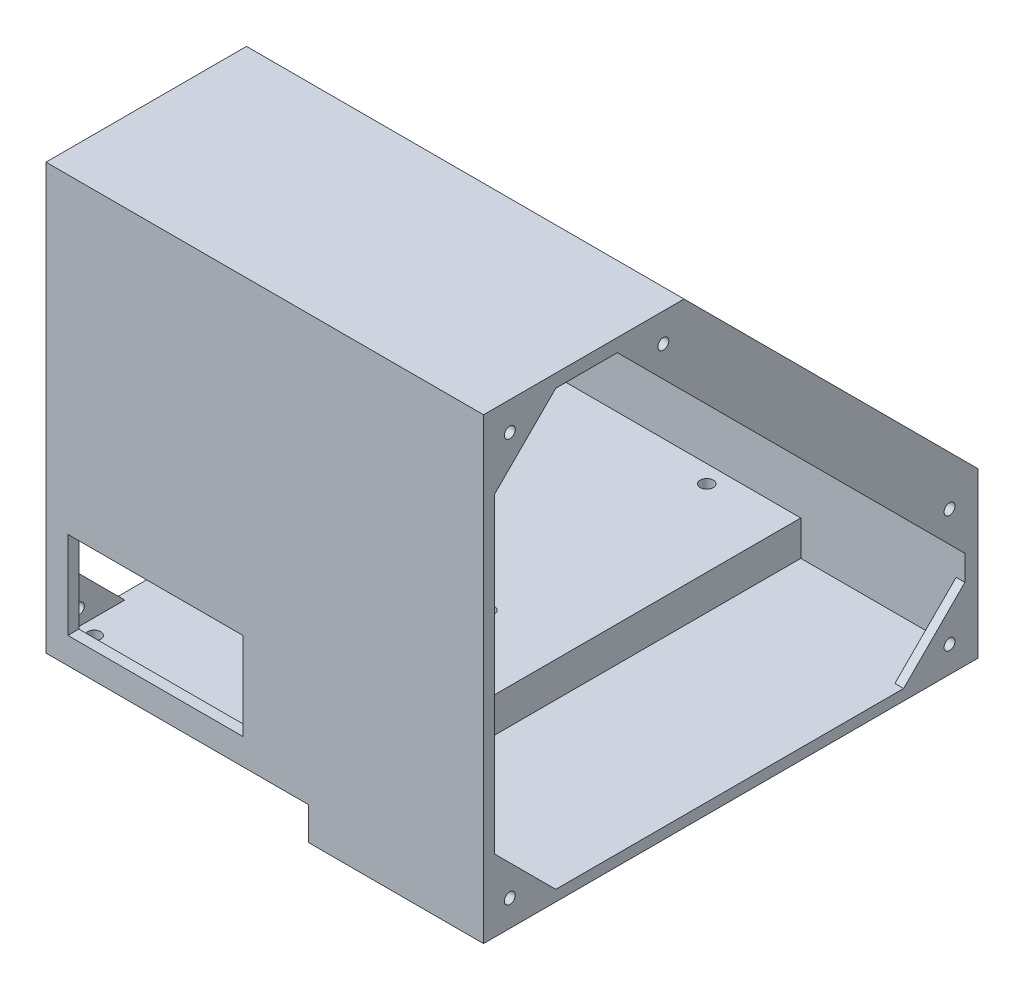
SolidWorks part; units mm, degrees
ref_plane "Front Plane" through (0, 0, 0) normal (0, 0, 1) x (1, 0, 0)
ref_plane "Top Plane" through (0, 0, 0) normal (0, 1, 0) x (1, 0, 0)
ref_plane "Right Plane" through (0, 0, 0) normal (1, 0, 0) x (0, 0, -1)
sketch "Sketch1" plane through (0, 0, 0) normal (1, 0, 0) x (0, 0, -1)
  line L0 (0, 0) -> (0, 30)
  line L1 (0, 30) -> (-67.1751, 97.1751)
  line L2 (-67.1751, 97.1751) -> (-113, 97.1751)
  line L3 (-113, 97.1751) -> (-113, 94.1751)
  line L4 (-113, 94.1751) -> (-68.4178, 94.1751)
  line L5 (-68.4178, 94.1751) -> (-3, 28.7574)
  line L6 (-3, 28.7574) -> (-3, 0)
  line L7 (-3, 0) -> (0, 0)
  line L8 (-3, 28.7574) -> (0, 28.7574) construction
  line L9 (-3, 28.7574) -> (-0.8787, 30.8787) construction
  line L10 (-68.4178, 94.1751) -> (-68.4178, 97.1751) construction
  point P3 (-68.4178, 90.8281)
  point P14 (-66.2965, 92.1818)
  dimension "D1" = 95
  dimension "D2" = 135
  dimension "D3" = 3
  dimension "D4" = 30
  dimension "D5" = 110
extrude "Boss-Extrude1" add sketch "Sketch1" along normal blind 100
sketch "Sketch2" plane through (0, 0, 0) normal (0, -1, 0) x (1, 0, 0)
  line L0 (100, 0) -> (0, 0) construction
  line L1 (100, 3) -> (60, 3)
  line L2 (100, 3) -> (100, 0)
  line L3 (100, 0) -> (60, 0)
  line L4 (60, 3) -> (60, 0)
  dimension "D1" = 40
extrude "Boss-Extrude2" add sketch "Sketch2" along normal blind 7.5
sketch "Sketch3" plane through (0, 0, 0) normal (0, -1, 0) x (1, 0, 0)
  line L0 (0, 3) -> (0, 113)
  line L1 (0, 113) -> (60, 113)
  line L2 (60, 113) -> (60, 3)
  line L3 (60, 3) -> (0, 3)
  line L4 (100, 3) -> (0, 3) construction
  line L5 (60, 3) -> (0, 3) construction
  point P4 (60, 3)
  dimension "D1" = 110
extrude "Boss-Extrude3" add sketch "Sketch3" against normal blind 3
sketch "Sketch4" plane through (0, 0, 3) normal (0, 0, 1) x (1, 0, 0)
  line L0 (60, 3) -> (60, -7.5)
  line L1 (60, -7.5) -> (100, -7.5)
  line L2 (100, -7.5) -> (100, -5)
  line L3 (100, 28.7574) -> (100, -7.5) construction
  line L4 (100, -5) -> (62.5, -5)
  line L5 (62.5, -5) -> (62.5, 3)
  line L6 (62.5, 3) -> (60, 3)
  dimension "D1" = 2.5
extrude "Boss-Extrude4" add sketch "Sketch4" along normal up to surface (110 mm away) up to face at (30, 1.5, 113)
sketch "Sketch5" plane through (0, 94.1751, 0) normal (0, -1, 0) x (1, 0, 0)
  line L0 (100, 113) -> (100, 68.4178) construction
  line L1 (0, 113) -> (100, 113)
  line L2 (0, 113) -> (0, 110.5)
  line L3 (0, 110.5) -> (100, 110.5)
  line L4 (100, 113) -> (100, 110.5)
  dimension "D1" = 2.5
extrude "Boss-Extrude5" add sketch "Sketch5" along normal up to next
sketch "Sketch6" plane through (0, 0, 0) normal (0, -1, 0) x (1, 0, 0)
  circle A0 centre (5, 107) radius 1.5 construction
  circle A1 centre (45, 107) radius 1.5 construction
  circle A2 centre (45, 57) radius 1.5 construction
  circle A3 centre (5, 57) radius 1.5 construction
  circle A4 centre (5, 7) radius 1.5 construction
  circle A5 centre (45, 7) radius 1.5 construction
  circle A6 centre (5, 107) radius 1.5
  circle A7 centre (45, 107) radius 1.5
  circle A8 centre (45, 57) radius 1.5
  circle A9 centre (5, 57) radius 1.5
  circle A10 centre (5, 7) radius 1.5
  circle A11 centre (45, 7) radius 1.5
extrude "Cut-Extrude1" cut sketch "Sketch6" against normal up to next
sketch "Sketch7" plane through (100, 0, 0) normal (1, 0, 0) x (0, 0, -1)
  line L0 (-110.5, -5) -> (-110.5, 9)
  line L1 (-110.5, -5) -> (-110.5, 94.1751) construction
  line L2 (-110.5, 9) -> (-96.5, -5)
  line L3 (-110.5, -5) -> (-3, -5) construction
  line L4 (-96.5, -5) -> (-110.5, -5)
  line L5 (-110.5, 94.1751) -> (-110.5, 80.1751)
  line L6 (-110.5, 80.1751) -> (-96.5, 94.1751)
  line L7 (-110.5, 94.1751) -> (-68.4178, 94.1751) construction
  line L8 (-96.5, 94.1751) -> (-110.5, 94.1751)
  line L9 (-82.4178, 94.1751) -> (-3, 14.7574)
  line L10 (-3, 28.7574) -> (-3, -5) construction
  line L11 (-3, 14.7574) -> (-3, 28.7574)
  line L12 (-3, 28.7574) -> (-68.4178, 94.1751)
  line L13 (-68.4178, 94.1751) -> (-82.4178, 94.1751)
  line L14 (-17, -5) -> (-3, 9)
  line L15 (-3, 9) -> (-3, -5)
  line L16 (-3, -5) -> (-17, -5)
  line L17 (-110.5, -5) -> (-103.5, 2) construction
  line L18 (-3, -5) -> (-10, 2) construction
  line L19 (-3, 28.7574) -> (-10, 21.7574) construction
  line L20 (-68.4178, 94.1751) -> (-75.4178, 87.1751) construction
  line L21 (-110.5, 94.1751) -> (-103.5, 87.1751) construction
  circle A0 centre (-107, -1.5) radius 1.25
  circle A1 centre (-6.5, -1.5) radius 1 construction
  circle A2 centre (-6.5, -1.5) radius 1.25
  circle A3 centre (-6.5, 25.2574) radius 1.25
  circle A4 centre (-71.9178, 90.6751) radius 1.25
  circle A5 centre (-107, 90.6751) radius 1.25
  dimension "D2" = 2
  dimension "D1" = 14
  dimension "D3" = 0.25
extrude "Boss-Extrude6" add sketch "Sketch7" against normal blind 2
sketch "Sketch8" plane through (0, 15, -15) normal (0, 0.7071, -0.7071) x (1, 0, 0)
  line L0 (96.675, -112.2132) -> (100, -112.2132) construction
  line L1 (96.675, -25.2132) -> (3.325, -25.2132) construction
  line L2 (96.675, -25.2132) -> (96.675, -112.2132) construction
  line L3 (96.675, -112.2132) -> (3.325, -112.2132) construction
  line L4 (3.325, -25.2132) -> (3.325, -112.2132) construction
  line L5 (100, -21.2132) -> (100, -116.2132) construction
  line L6 (96.675, -112.2132) -> (96.675, -116.2132) construction
  line L7 (100, -116.2132) -> (0, -116.2132) construction
  line L8 (3.325, -21.2132) -> (3.325, -25.2132) construction
  line L9 (100, -21.2132) -> (0, -21.2132) construction
  line L10 (3.325, -25.2132) -> (0, -25.2132) construction
  line L11 (0, -21.2132) -> (0, -116.2132) construction
  line L12 (96.675, -109.4882) -> (93.95, -109.4882) construction
  line L13 (93.95, -109.4882) -> (93.95, -112.2132) construction
  line L14 (93.95, -109.4882) -> (6.05, -109.4882) construction
  line L15 (6.05, -109.4882) -> (3.325, -109.4882) construction
  line L16 (93.95, -109.4882) -> (93.95, -44.5882) construction
  line L17 (93.95, -44.5882) -> (6.05, -44.5882) construction
  line L18 (6.05, -44.5882) -> (6.05, -109.4882) construction
  line L19 (89.025, -102.7132) -> (96.675, -102.7132) construction
  line L20 (89.025, -102.7132) -> (11.025, -102.7132)
  line L21 (89.025, -102.7132) -> (89.025, -58.8437)
  line L22 (89.025, -58.8437) -> (11.025, -58.8437)
  line L23 (11.025, -102.7132) -> (11.025, -58.8437)
  line L24 (89.025, -102.7132) -> (89.025, -112.2132) construction
  line L25 (51.495, -25.2132) -> (51.495, -33.7132) construction
  line L26 (51.495, -33.7132) -> (96.675, -33.7132) construction
  line L28 (33.175, -28.2132) -> (6.175, -28.2132)
  line L29 (33.175, -28.2132) -> (33.175, -40.2132)
  line L30 (33.175, -40.2132) -> (6.175, -40.2132)
  line L31 (6.175, -28.2132) -> (6.175, -40.2132)
  circle A0 centre (6.05, -109.4882) radius 1.5 construction
  circle A1 centre (6.05, -109.4882) radius 1.75
  circle A2 centre (93.95, -109.4882) radius 1.75
  circle A3 centre (93.95, -44.5882) radius 1.75
  circle A4 centre (6.05, -44.5882) radius 1.75
  circle A5 centre (51.495, -33.7132) radius 2.5
  dimension "D5" = 3
  dimension "D13" = 5
  dimension "D1" = 87
  dimension "D2" = 93.35
  dimension "D3" = 87.9
  dimension "D6" = 64.9
  dimension "D7" = 7.65
  dimension "D8" = 9.5
  dimension "D9" = 53.3695
  dimension "D10" = 85.65
  dimension "D11" = 8.5
  dimension "D12" = 45.18
  dimension "D14" = 63.5
  dimension "D15" = 90.5
  dimension "D16" = 27
  dimension "D17" = 3
  dimension "D18" = 12
  dimension "D4" = 0.25
extrude "Cut-Extrude2" cut sketch "Sketch8" against normal up to next
sketch "Sketch9" plane through (0, 12.8787, -12.8787) normal (0, -0.7071, 0.7071) x (1, 0, 0)
  line L0 (89.025, 58.8437) -> (89.025, 49.7132) construction
  line L1 (5.025, 49.7132) -> (92.025, 49.7132)
  line L2 (5.025, 49.7132) -> (5.025, 105.7132)
  line L3 (5.025, 105.7132) -> (92.025, 105.7132)
  line L4 (92.025, 49.7132) -> (92.025, 105.7132)
  line L5 (89.025, 58.8437) -> (92.025, 58.8437) construction
  line L6 (11.025, 102.7132) -> (11.025, 105.7132) construction
  line L7 (11.025, 102.7132) -> (5.025, 102.7132) construction
  line L8 (11.025, 102.7132) -> (89.025, 102.7132) construction
  line L9 (6.175, 28.2132) -> (33.175, 28.2132) construction
  line L10 (33.175, 28.2132) -> (33.175, 40.2132) construction
  line L11 (33.175, 40.2132) -> (6.175, 40.2132) construction
  line L12 (6.175, 40.2132) -> (6.175, 28.2132) construction
  line L13 (6.175, 28.2132) -> (33.175, 28.2132) construction
  line L14 (33.175, 28.2132) -> (33.175, 40.2132) construction
  line L15 (33.175, 40.2132) -> (6.175, 40.2132) construction
  line L16 (6.175, 40.2132) -> (6.175, 28.2132) construction
  line L17 (4.675, 26.7132) -> (34.675, 26.7132)
  line L18 (34.675, 26.7132) -> (34.675, 41.7132)
  line L19 (34.675, 41.7132) -> (4.675, 41.7132)
  line L20 (4.675, 41.7132) -> (4.675, 26.7132)
  point P22 (0, 0)
  dimension "D1" = 87
  dimension "D2" = 56
  dimension "D3" = 3
  dimension "D4" = 3
  dimension "D5" = 1.5
extrude "Cut-Extrude3" cut sketch "Sketch9" against normal offset from surface (2 mm away) 1 up to face at (93.95, 93.6573, 63.6573)
sketch "Sketch10" plane through (0, 0, 110.5) normal (0, 0, -1) x (-1, 0, 0)
  line L0 (-5, 3) -> (-5, 6) construction
  line L1 (-5, 6) -> (-45, 6)
  line L2 (-5, 6) -> (-5, 26)
  line L3 (-5, 26) -> (-45, 26)
  line L4 (-45, 6) -> (-45, 26)
  line L5 (-62.5, 3) -> (0, 3) construction
  line L6 (-5, 6) -> (0, 6) construction
  line L7 (0, 3) -> (0, 94.1751) construction
  dimension "D1" = 3
  dimension "D2" = 5
  dimension "D3" = 40
  dimension "D4" = 20
extrude "Cut-Extrude4" cut sketch "Sketch10" against normal through all
sketch "Sketch11" plane through (0, 0, 0) normal (-1, 0, 0) x (0, 0, 1)
  line L0 (110.5, 94.1751) -> (110.5, 80.1751) construction
  line L1 (110.5, 80.1751) -> (96.5, 94.1751) construction
  line L2 (96.5, 94.1751) -> (110.5, 94.1751) construction
  line L3 (68.4178, 94.1751) -> (82.4178, 94.1751) construction
  line L4 (3, 28.7574) -> (68.4178, 94.1751) construction
  line L5 (82.4178, 94.1751) -> (3, 14.7574) construction
  line L6 (3, 14.7574) -> (3, 28.7574) construction
  line L7 (110.5, 94.1751) -> (110.5, 80.1751)
  line L8 (110.5, 80.1751) -> (96.5, 94.1751)
  line L9 (96.5, 94.1751) -> (110.5, 94.1751)
  line L10 (68.4178, 94.1751) -> (82.4178, 94.1751)
  line L11 (3, 28.7574) -> (68.4178, 94.1751)
  line L12 (82.4178, 94.1751) -> (4.1213, 15.8787)
  line L13 (3, 14.7574) -> (3, 28.7574)
  line L17 (110.5, 3) -> (3, 3) construction
  line L18 (17, 3) -> (3, 3)
  line L19 (96.5, 3) -> (110.5, 17)
  line L20 (110.5, 3) -> (110.5, 94.1751) construction
  line L21 (110.5, 17) -> (110.5, 3)
  line L22 (110.5, 3) -> (96.5, 3)
  line L23 (4.1213, 15.8787) -> (3, 14.7574) construction
  line L24 (4.1213, 15.8787) -> (17, 3)
  line L25 (3, 14.7574) -> (3, 3)
  line L26 (3, 3) -> (10, 10) construction
  line L27 (110.5, 3) -> (103.5, 10) construction
  circle A0 centre (71.9178, 90.6751) radius 1.25 construction
  circle A1 centre (107, 90.6751) radius 1.25 construction
  circle A2 centre (6.5, 25.2574) radius 1.25 construction
  circle A3 centre (71.9178, 90.6751) radius 1.25
  circle A4 centre (107, 90.6751) radius 1.25
  circle A5 centre (6.5, 25.2574) radius 1.25
  circle A6 centre (107, 6.5) radius 1.25
  circle A7 centre (6.5, 6.5) radius 1.25
extrude "Boss-Extrude7" add sketch "Sketch11" against normal blind 1.5
sketch "Sketch12" plane through (0, 0, 0) normal (-1, 0, 0) x (0, 0, 1)
  line L0 (21.2132, 49.0919) -> (55.1543, 83.033)
  line L1 (21.2132, 49.0919) -> (26.163, 44.1421)
  line L2 (55.1543, 83.033) -> (60.1041, 78.0833)
  line L3 (26.163, 44.1421) -> (60.1041, 78.0833)
  line L4 (22.2739, 48.0312) -> (61.8718, 87.6292) construction
  point P6 (38.9825, 34.0512)
  point P8 (20.8325, 49.4726)
  dimension "D1" = 1.5
  dimension "D2" = 7
  dimension "D3" = 48
extrude "Cut-Extrude5" cut sketch "Sketch12" against normal up to next
equation "\"Tolerance\" = 0.25mm"
equation "\"Pocket_Head_M5\"= 8mm"
equation "\"Pocket_Head_M4\" = 7mm"
equation "\"Pocket_Nut_M4\" = 7mm"
equation "\"Pocket_Nut_M2.5\" = 5mm"
equation "\"Pocket_Nut_M5\"= 8mm"
equation "\"Pocket_Nut_M3\"= 5.5mm"
equation "\"Pocket_Head_M3\"= 5.5mm"
equation "\"Pocket_Head_M2.5\" = 4.7mm"
equation "\"Pocket_Head_M6\" = 10mm"
equation "\"D3@Sketch7\"=\"Tolerance\""
equation "\"D4@Sketch8\"=\"Tolerance\""
